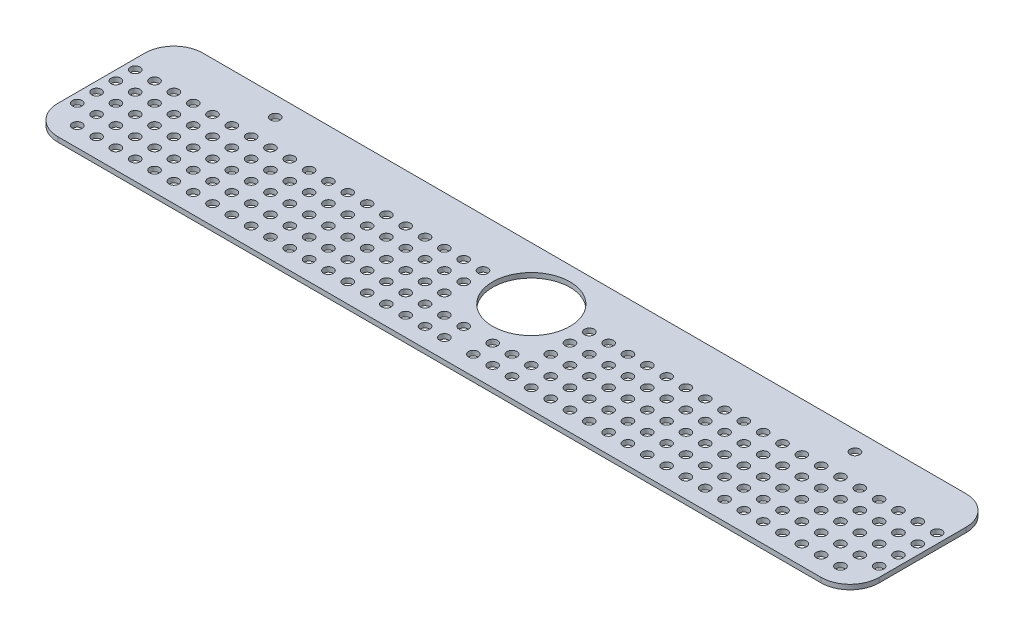
SolidWorks part; units mm, degrees
ref_plane "Front Plane" through (0, 0, 0) normal (0, 0, 1) x (1, 0, 0)
ref_plane "Top Plane" through (0, 0, 0) normal (0, 1, 0) x (1, 0, 0)
ref_plane "Right Plane" through (0, 0, 0) normal (1, 0, 0) x (0, 0, -1)
sketch "Sketch1" plane through (0, 0, 0) normal (0, 1, 0) x (1, 0, 0)
  line L0 (-415.0151, 97.0124) -> (383.6515, 97.0124) construction
  line L1 (395, -75) -> (-395, -75)
  line L2 (425, -45) -> (425, 45)
  line L3 (395, 75) -> (-395, 75)
  line L4 (-425, -45) -> (-425, 45)
  line L5 (425, -75) -> (-425, 75) construction
  line L6 (425, 75) -> (-425, -75) construction
  line L7 (0, -75) -> (0, 75) construction
  line L12 (-460.1751, 35) -> (182.6933, 35) construction
  line L13 (-460.1751, -65) -> (182.6933, -65) construction
  line L14 (-415, 25) -> (-395, 25) construction
  arc A0 (425, 45) -> (395, 75) centre (395, 45) ccw
  arc A1 (425, -45) -> (395, -75) centre (395, -45) cw
  arc A2 (-395, -75) -> (-425, -45) centre (-395, -45) cw
  arc A3 (-425, 45) -> (-395, 75) centre (-395, 45) cw
  circle A8 centre (0, 20) radius 40
  circle A25 centre (-300, 55) radius 5
  circle A26 centre (300, 55) radius 5
  circle A27 centre (0, 20) radius 30 construction
  circle A28 centre (-415, 25) radius 10 construction
  circle A29 centre (-415, 25) radius 5
  circle A30 centre (-395, 25) radius 5
  circle A31 centre (-375, 25) radius 5
  circle A32 centre (-355, 25) radius 5
  circle A33 centre (-335, 25) radius 5
  circle A34 centre (-315, 25) radius 5
  circle A35 centre (-295, 25) radius 5
  circle A36 centre (-275, 25) radius 5
  circle A37 centre (-255, 25) radius 5
  circle A38 centre (-235, 25) radius 5
  circle A39 centre (-415, 5) radius 5
  circle A40 centre (-395, 5) radius 5
  circle A41 centre (-375, 5) radius 5
  circle A42 centre (-355, 5) radius 5
  circle A43 centre (-335, 5) radius 5
  circle A44 centre (-315, 5) radius 5
  circle A45 centre (-295, 5) radius 5
  circle A46 centre (-275, 5) radius 5
  circle A47 centre (-255, 5) radius 5
  circle A48 centre (-235, 5) radius 5
  circle A49 centre (-415, -15) radius 5
  circle A50 centre (-395, -15) radius 5
  circle A51 centre (-375, -15) radius 5
  circle A52 centre (-355, -15) radius 5
  circle A53 centre (-335, -15) radius 5
  circle A54 centre (-315, -15) radius 5
  circle A55 centre (-295, -15) radius 5
  circle A56 centre (-275, -15) radius 5
  circle A57 centre (-255, -15) radius 5
  circle A58 centre (-235, -15) radius 5
  circle A59 centre (-415, -35) radius 5
  circle A60 centre (-395, -35) radius 5
  circle A61 centre (-375, -35) radius 5
  circle A62 centre (-355, -35) radius 5
  circle A63 centre (-335, -35) radius 5
  circle A64 centre (-315, -35) radius 5
  circle A65 centre (-295, -35) radius 5
  circle A66 centre (-275, -35) radius 5
  circle A67 centre (-255, -35) radius 5
  circle A68 centre (-235, -35) radius 5
  circle A70 centre (-395, -55) radius 5
  circle A71 centre (-375, -55) radius 5
  circle A72 centre (-355, -55) radius 5
  circle A73 centre (-335, -55) radius 5
  circle A74 centre (-315, -55) radius 5
  circle A75 centre (-295, -55) radius 5
  circle A76 centre (-275, -55) radius 5
  circle A77 centre (-255, -55) radius 5
  circle A78 centre (-235, -55) radius 5
  circle A79 centre (-415, -55) radius 5 [skipped]
  circle A80 centre (-215, -35) radius 5
  circle A81 centre (-215, -55) radius 5
  circle A82 centre (-195, -35) radius 5
  circle A83 centre (-195, -55) radius 5
  circle A84 centre (195, -55) radius 5
  circle A85 centre (215, -55) radius 5
  circle A86 centre (235, -55) radius 5
  circle A87 centre (255, -55) radius 5
  circle A88 centre (275, -55) radius 5
  circle A89 centre (295, -55) radius 5
  circle A90 centre (315, -55) radius 5
  circle A91 centre (295, -35) radius 5
  circle A92 centre (275, -35) radius 5
  circle A93 centre (255, -35) radius 5
  circle A94 centre (235, -35) radius 5
  circle A95 centre (195, -35) radius 5
  circle A96 centre (215, -35) radius 5
  circle A97 centre (235, -15) radius 5
  circle A98 centre (255, -15) radius 5
  circle A99 centre (275, -15) radius 5
  circle A100 centre (295, -15) radius 5
  circle A101 centre (295, 5) radius 5
  circle A102 centre (275, 5) radius 5
  circle A103 centre (255, 5) radius 5
  circle A104 centre (235, 5) radius 5
  circle A105 centre (235, 25) radius 5
  circle A106 centre (255, 25) radius 5
  circle A107 centre (275, 25) radius 5
  circle A108 centre (295, 25) radius 5
  circle A109 centre (315, 25) radius 5
  circle A110 centre (315, 5) radius 5
  circle A111 centre (315, -15) radius 5
  circle A112 centre (315, -35) radius 5
  circle A113 centre (335, -55) radius 5
  circle A114 centre (335, 5) radius 5
  circle A115 centre (335, -15) radius 5
  circle A116 centre (335, -35) radius 5
  circle A117 centre (355, -55) radius 5
  circle A118 centre (355, -35) radius 5
  circle A119 centre (355, -15) radius 5
  circle A120 centre (355, 5) radius 5
  circle A121 centre (335, 25) radius 5
  circle A122 centre (355, 25) radius 5
  circle A123 centre (375, -55) radius 5
  circle A124 centre (375, -15) radius 5
  circle A125 centre (375, -35) radius 5
  circle A126 centre (395, -55) radius 5
  circle A127 centre (395, -35) radius 5
  circle A128 centre (395, -15) radius 5
  circle A129 centre (415, -35) radius 5
  circle A130 centre (415, -15) radius 5
  circle A131 centre (415, 5) radius 5
  circle A132 centre (395, 5) radius 5
  circle A133 centre (375, 5) radius 5
  circle A134 centre (375, 25) radius 5
  circle A135 centre (395, 25) radius 5
  circle A136 centre (415, 25) radius 5
  circle A137 centre (-215, 25) radius 5
  circle A138 centre (-215, 5) radius 5
  circle A139 centre (-215, -15) radius 5
  circle A140 centre (-175, -35) radius 5
  circle A141 centre (-175, -55) radius 5
  circle A142 centre (-195, 25) radius 5
  circle A143 centre (-195, 5) radius 5
  circle A144 centre (-195, -15) radius 5
  circle A145 centre (-155, -35) radius 5
  circle A146 centre (-155, -55) radius 5
  circle A147 centre (-175, 25) radius 5
  circle A148 centre (-175, 5) radius 5
  circle A149 centre (-175, -15) radius 5
  circle A150 centre (-135, -35) radius 5
  circle A151 centre (-135, -55) radius 5
  circle A152 centre (-155, 25) radius 5
  circle A153 centre (-155, 5) radius 5
  circle A154 centre (-155, -15) radius 5
  circle A155 centre (-115, -35) radius 5
  circle A156 centre (-115, -55) radius 5
  circle A157 centre (-135, 25) radius 5
  circle A158 centre (-135, 5) radius 5
  circle A159 centre (-135, -15) radius 5
  circle A160 centre (-95, -35) radius 5
  circle A161 centre (-95, -55) radius 5
  circle A162 centre (-115, 25) radius 5
  circle A163 centre (-115, 5) radius 5
  circle A164 centre (-115, -15) radius 5
  circle A165 centre (-75, -35) radius 5
  circle A166 centre (-75, -55) radius 5
  circle A167 centre (-95, 25) radius 5
  circle A168 centre (-95, 5) radius 5
  circle A169 centre (-95, -15) radius 5
  circle A170 centre (-55, -35) radius 5
  circle A171 centre (-55, -55) radius 5
  circle A172 centre (-75, 25) radius 5
  circle A173 centre (-75, 5) radius 5
  circle A174 centre (-75, -15) radius 5
  circle A175 centre (-35, -35) radius 5
  circle A176 centre (-35, -55) radius 5
  circle A177 centre (-55, 25) radius 5
  circle A178 centre (-55, 5) radius 5
  circle A179 centre (-55, -15) radius 5
  circle A180 centre (-15, -35) radius 5
  circle A181 centre (-15, -55) radius 5
  circle A182 centre (215, 25) radius 5
  circle A183 centre (215, 5) radius 5
  circle A184 centre (215, -15) radius 5
  circle A185 centre (175, -35) radius 5
  circle A186 centre (175, -55) radius 5
  circle A187 centre (195, 25) radius 5
  circle A188 centre (195, 5) radius 5
  circle A189 centre (195, -15) radius 5
  circle A190 centre (155, -35) radius 5
  circle A191 centre (155, -55) radius 5
  circle A192 centre (175, 25) radius 5
  circle A193 centre (175, 5) radius 5
  circle A194 centre (175, -15) radius 5
  circle A195 centre (135, -35) radius 5
  circle A196 centre (135, -55) radius 5
  circle A197 centre (155, 25) radius 5
  circle A198 centre (155, 5) radius 5
  circle A199 centre (155, -15) radius 5
  circle A200 centre (115, -35) radius 5
  circle A201 centre (115, -55) radius 5
  circle A202 centre (135, 25) radius 5
  circle A203 centre (135, 5) radius 5
  circle A204 centre (135, -15) radius 5
  circle A205 centre (95, -35) radius 5
  circle A206 centre (95, -55) radius 5
  circle A207 centre (115, 25) radius 5
  circle A208 centre (115, 5) radius 5
  circle A209 centre (115, -15) radius 5
  circle A210 centre (75, -35) radius 5
  circle A211 centre (75, -55) radius 5
  circle A212 centre (95, 25) radius 5
  circle A213 centre (95, 5) radius 5
  circle A214 centre (95, -15) radius 5
  circle A215 centre (55, -35) radius 5
  circle A216 centre (55, -55) radius 5
  circle A217 centre (75, 25) radius 5
  circle A218 centre (75, 5) radius 5
  circle A219 centre (75, -15) radius 5
  circle A220 centre (35, -35) radius 5
  circle A221 centre (35, -55) radius 5
  circle A222 centre (55, 25) radius 5
  circle A223 centre (55, 5) radius 5
  circle A224 centre (55, -15) radius 5
  circle A225 centre (15, -35) radius 5
  circle A226 centre (15, -55) radius 5
  point P0 (0, 0)
  point P29 (0, 50)
  point P33 (-425, 25)
  point P35 (-415, 35)
  dimension "D3" = 30
  dimension "D4" = 40
  dimension "D5" = 80
  dimension "D8" = 125
  dimension "D9" = 30
  dimension "D10" = 25
  dimension "D11" = 10
  dimension "D12" = 20
  dimension "D6" = 10
  dimension "D7" = 20
  dimension "D15" = 60
  dimension "D18" = 20
  dimension "D19" = 10
  dimension "D1" = 850
  dimension "D2" = 150
  dimension "D13" = 125
  dimension "D14" = 10
  dimension "D16" = 100
  dimension "D17" = 425
  dimension "D21" = 20
  dimension "D20" = 10
  dimension "D22" = 5
  dimension "D23" = 3
  dimension "D24" = 10
  dimension "D25" = 10
extrude "Boss-Extrude1" add sketch "Sketch1" along normal blind 5
